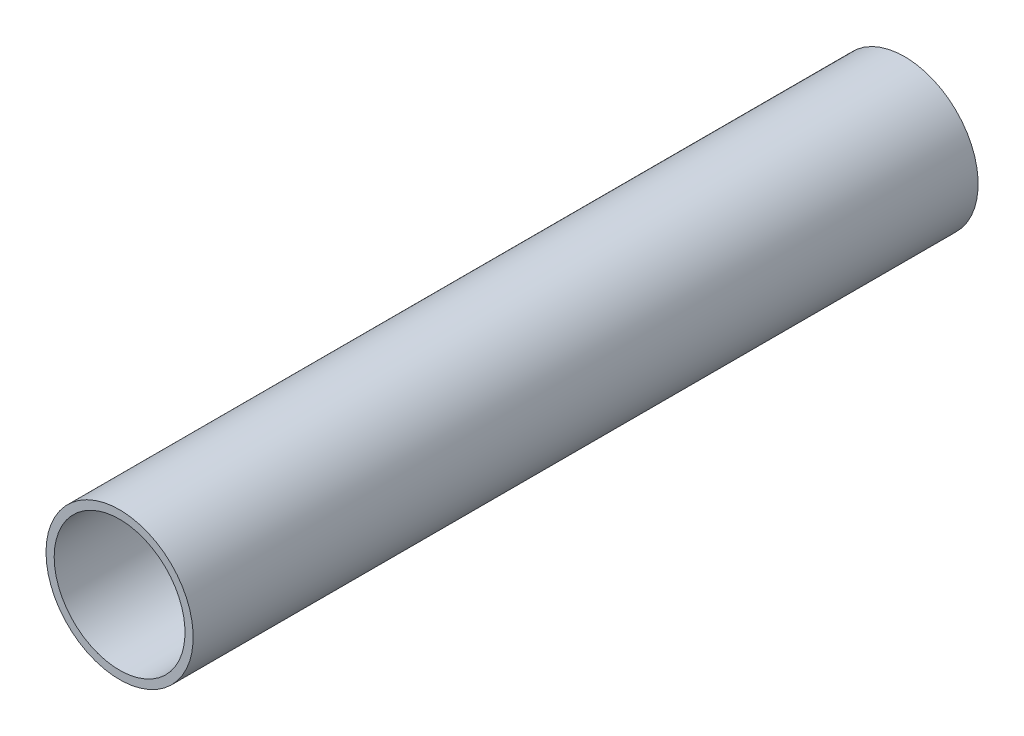
SolidWorks part; units mm, degrees
ref_plane "Front Plane" through (0, 0, 0) normal (0, 0, 1) x (1, 0, 0)
ref_plane "Top Plane" through (0, 0, 0) normal (0, 1, 0) x (1, 0, 0)
ref_plane "Right Plane" through (0, 0, 0) normal (1, 0, 0) x (0, 0, -1)
sketch "Sketch1" plane through (0, 0, 0) normal (0, 0, 1) x (1, 0, 0)
  line L0 (-57.15, 0) -> (57.15, 0) construction
  line L1 (0, -57.15) -> (0, 57.15) construction
  circle A0 centre (0, 0) radius 57.15
  circle A1 centre (0, 0) radius 50.8
  point P4 (0, 0)
  point P9 (0, 0)
  point P10 (50.8, 0)
  dimension "D1" = 101.6
  dimension "OD" = 114.3
  dimension "Wall Thickness" = 6.35
sketch "Sketch2" plane through (0, 0, 0) normal (1, 0, 0) x (0, 0, -1)
  line L0 (304.8, 57.15) -> (-304.8, 57.15) construction
  line L1 (0, 57.15) -> (0, -57.15) construction
  point P3 (-173.355, 57.15)
  point P4 (0, 57.15)
  point P5 (173.355, 57.15)
  dimension "D1" = 131.445
  dimension "D2" = 131.445
  dimension "Length" = 609.6
sketch "Sketch3" plane through (0, 0, 0) normal (0, 0, 1) x (1, 0, 0)
  line L0 (0, -57.15) -> (0, 57.15) construction
  circle A0 centre (0, 0) radius 57.15
  circle A1 centre (0, 0) radius 50.8
  circle A2 centre (0, 0) radius 50.8 construction
extrude "Boss-Extrude1" add sketch "Sketch3" along normal mid plane 609.6
equation "\"D1@Boss-Extrude1\" = \"Length@Sketch2\""
equation "\"D1@Sketch2\"=\"OD@Sketch1\"*1.15"
equation "\"D2@Sketch2\"=\"D1@Sketch2\""
